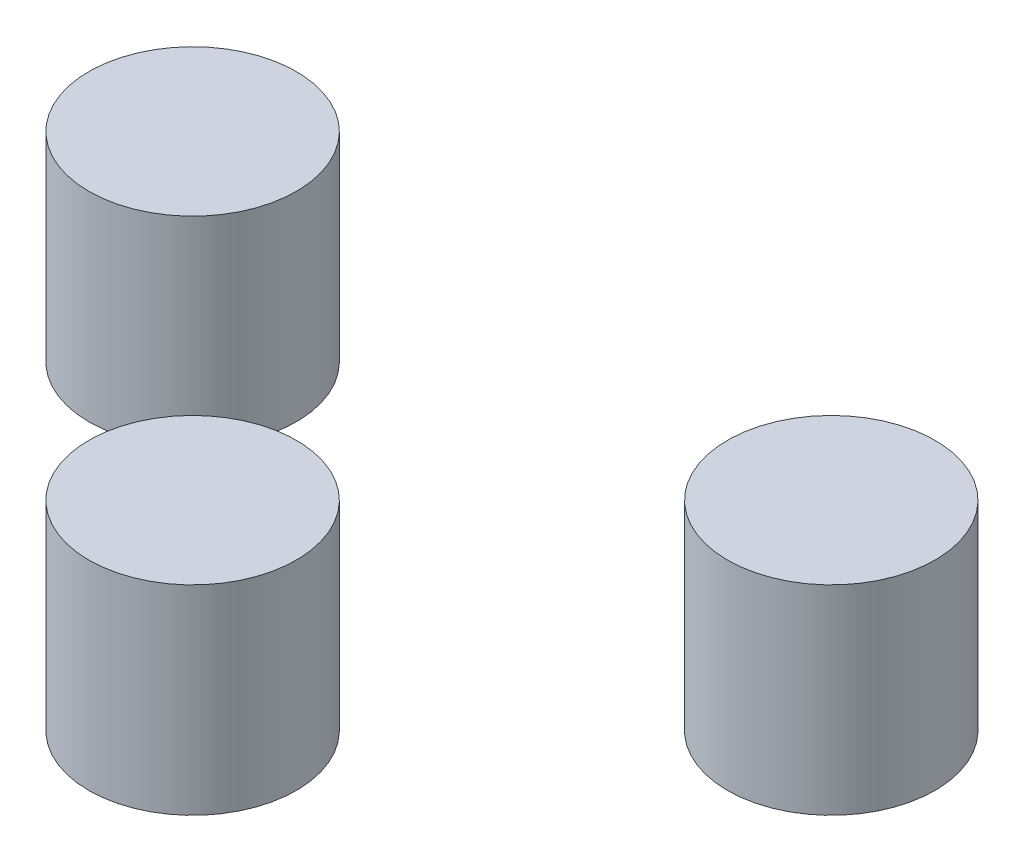
SolidWorks part; units mm, degrees
ref_plane "Front Plane" through (0, 0, 0) normal (0, 0, 1) x (1, 0, 0)
ref_plane "Top Plane" through (0, 0, 0) normal (0, 1, 0) x (1, 0, 0)
ref_plane "Right Plane" through (0, 0, 0) normal (1, 0, 0) x (0, 0, -1)
sketch "Sketch1" plane through (0, 0, 0) normal (0, 1, 0) x (1, 0, 0)
  circle A0 centre (-400, 1640) radius 130
extrude "Boss-Extrude1" add sketch "Sketch1" along normal blind 250 from offset 205
sketch "Sketch2" plane through (0, 0, 0) normal (0, 1, 0) x (1, 0, 0)
  circle A0 centre (400, 1640) radius 130
extrude "Boss-Extrude2" add sketch "Sketch2" along normal blind 250 from offset 205
sketch "Sketch3" plane through (0, 0, 0) normal (0, 1, 0) x (1, 0, 0)
  circle A0 centre (0, 1240) radius 130
extrude "Boss-Extrude3" add sketch "Sketch3" along normal blind 250 from offset 205
